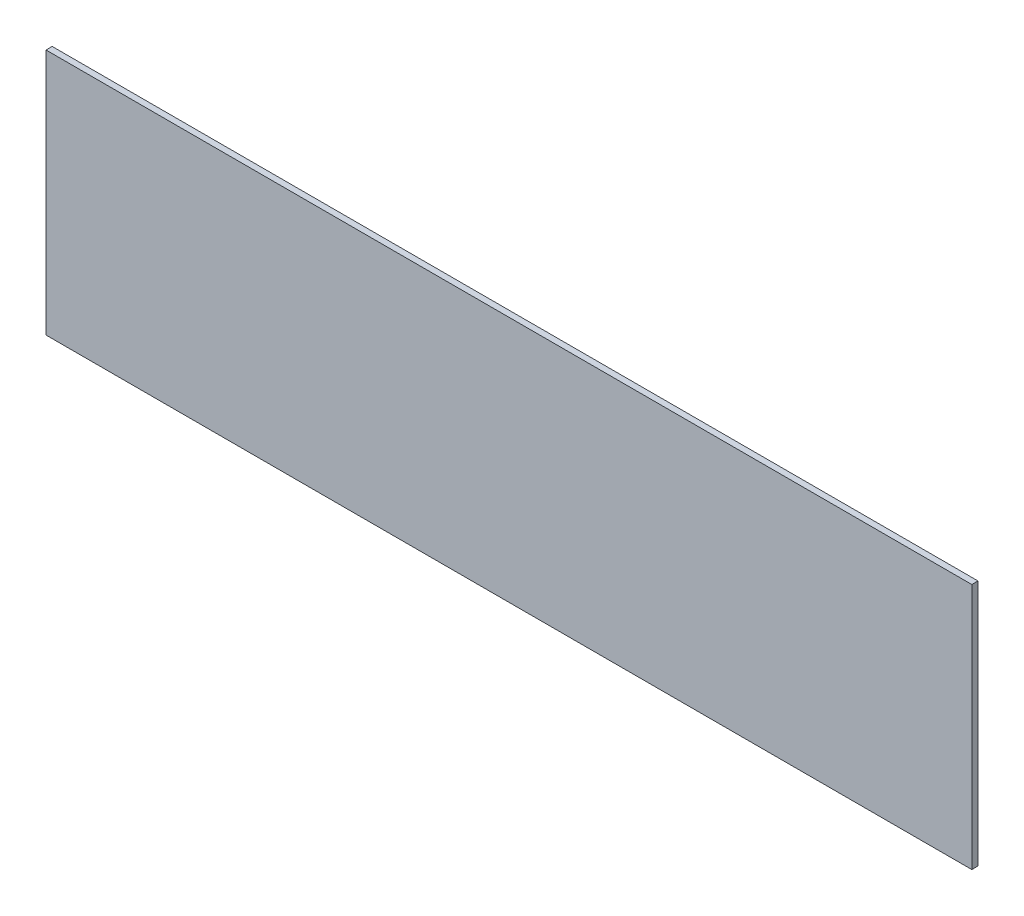
SolidWorks part; units mm, degrees
ref_plane "Front Plane" through (0, 0, 0) normal (0, 0, 1) x (1, 0, 0)
ref_plane "Top Plane" through (0, 0, 0) normal (0, 1, 0) x (1, 0, 0)
ref_plane "Right Plane" through (0, 0, 0) normal (1, 0, 0) x (0, 0, -1)
sketch "Sketch1" plane through (0, 0, 0) normal (0, 0, 1) x (1, 0, 0)
  line L1 (750, -200) -> (-750, -200)
  line L2 (750, -200) -> (750, 200)
  line L3 (750, 200) -> (-750, 200)
  line L4 (-750, -200) -> (-750, 200)
  line L5 (750, -200) -> (-750, 200) construction
  line L6 (750, 200) -> (-750, -200) construction
  point P0 (0, 0)
extrude "Boss-Extrude1" add sketch "Sketch1" along normal blind 10
